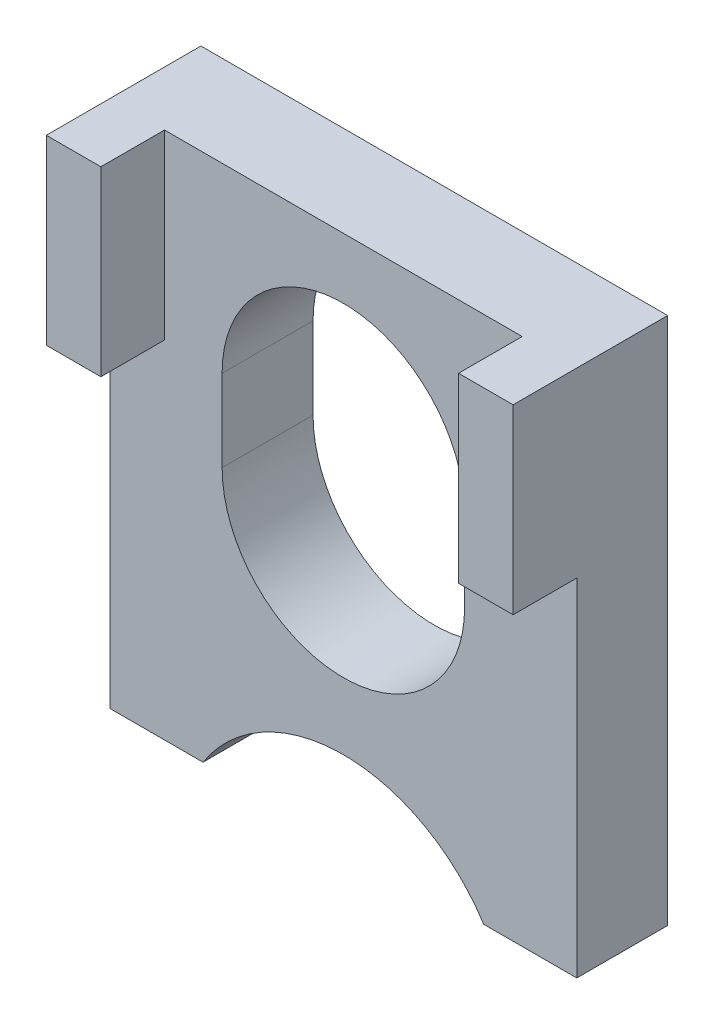
SolidWorks part; units mm, degrees
ref_plane "Спереди" through (0, 0, 0) normal (0, 0, 1) x (1, 0, 0)
ref_plane "Сверху" through (0, 0, 0) normal (0, 1, 0) x (1, 0, 0)
ref_plane "Справа" through (0, 0, 0) normal (1, 0, 0) x (0, 0, -1)
sketch "Эскиз1" plane through (0, 0, 0) normal (0, 0, 1) x (1, 0, 0)
  line L1 (-7.7, 13.7375) -> (7.7, 13.7375)
  line L5 (-7.7, 13.7375) -> (-7.7, -0.0396)
  line L6 (7.7, 13.7375) -> (7.7, -0.0396)
  line L7 (-7.7, -0.0396) -> (-7.7, -3.6899)
  line L8 (-7.7, -3.6899) -> (-4.6298, -3.6899)
  line L9 (0, 7.7375) -> (0, 5.041) construction
  line L10 (4, 7.7375) -> (4, 5.041)
  line L11 (-4, 7.7375) -> (-4, 5.041)
  line L12 (7.7, -0.0396) -> (7.7, -3.6899)
  line L13 (7.7, -3.6899) -> (4.6298, -3.6899)
  arc A0 (-4.6298, -3.6899) -> (4.6298, -3.6899) centre (0, -6.659) cw
  arc A1 (4, 7.7375) -> (-4, 7.7375) centre (0, 7.7375) ccw
  arc A2 (-4, 5.041) -> (4, 5.041) centre (0, 5.041) ccw
  point P1 (0, 6.3893)
  point P15 (0, 11.7375)
  point P16 (0, 1.041)
  dimension "D1" = 5.5
  dimension "D5" = 4
  dimension "D4" = 2.2
  dimension "D2" = 15.4
  dimension "D3" = 7.7
  dimension "D6" = 10.6965
  dimension "D7" = 2
  dimension "D8" = 7.7
extrude "Бобышка-Вытянуть1" add sketch "Эскиз1" along normal blind 3
sketch "Эскиз2" plane through (0, 0, 3) normal (0, 0, 1) x (1, 0, 0)
  line L1 (-7.7, 13.7375) -> (-5.9, 13.7375)
  line L2 (-7.7, 13.7375) -> (-7.7, 7.7375)
  line L3 (-7.7, 7.7375) -> (-5.9, 7.7375)
  line L4 (-5.9, 13.7375) -> (-5.9, 7.7375)
  line L5 (7.7, 13.7375) -> (5.9, 13.7375)
  line L6 (7.7, 13.7375) -> (7.7, 7.7375)
  line L7 (7.7, 7.7375) -> (5.9, 7.7375)
  line L8 (5.9, 13.7375) -> (5.9, 7.7375)
  dimension "D1" = 1.8
  dimension "D2" = 1.8
  dimension "D3" = 6
  dimension "D4" = 6
extrude "Бобышка-Вытянуть2" add sketch "Эскиз2" along normal blind 2.1
